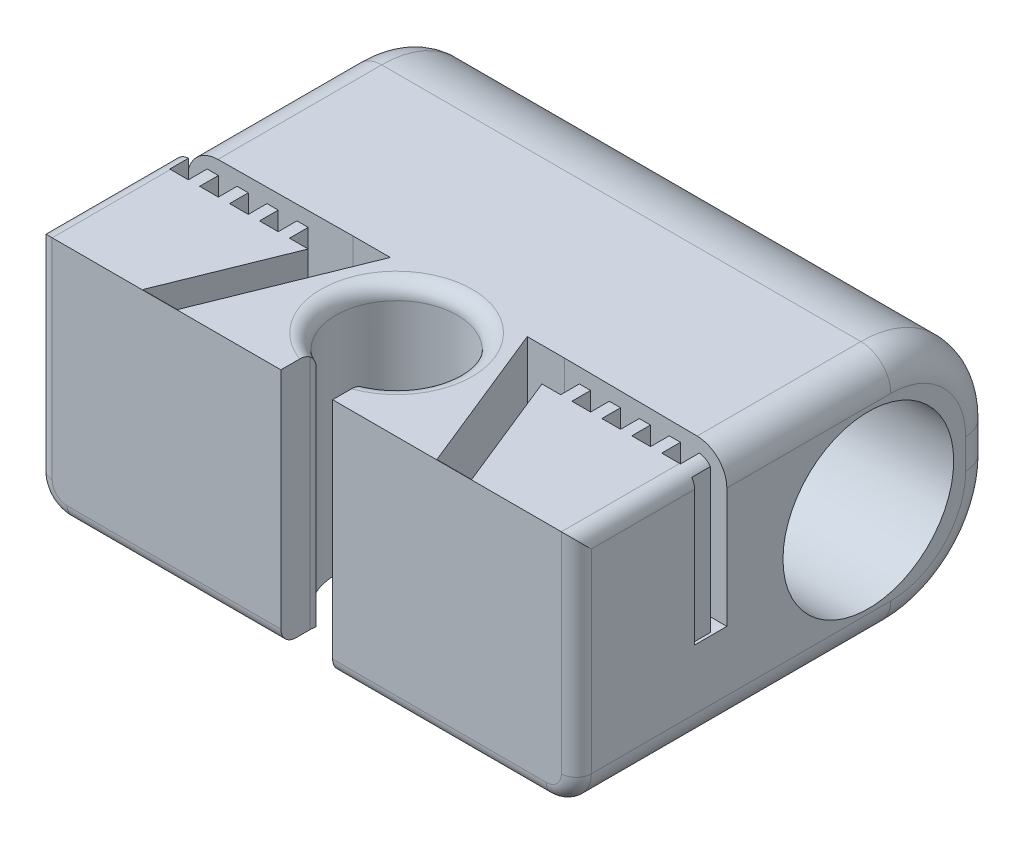
SolidWorks part; units mm, degrees
ref_plane "Alzado" through (0, 0, 0) normal (0, 0, 1) x (1, 0, 0)
ref_plane "Planta" through (0, 0, 0) normal (0, 1, 0) x (1, 0, 0)
ref_plane "Vista lateral" through (0, 0, 0) normal (1, 0, 0) x (0, 0, -1)
sketch "Croquis1" plane through (0, 0, 0) normal (0, 1, 0) x (1, 0, 0)
  line L0 (-16.125, -12.8625) -> (37.0847, -12.8625) construction
  line L1 (-16.125, 9.1375) -> (19.875, 9.1375)
  line L2 (-16.125, 9.1375) -> (-16.125, -18.8625)
  line L3 (-16.125, -18.8625) -> (0.1467, -18.8625)
  line L4 (19.875, 9.1375) -> (19.875, -18.8625)
  line L5 (19.875, 9.1375) -> (-16.125, -18.8625) construction
  line L6 (1.875, -16.9125) -> (1.875, -18.8125) construction
  line L7 (3.6033, -16.9125) -> (3.6033, -18.8625)
  line L8 (0.1467, -16.9125) -> (0.1467, -18.8625)
  line L9 (3.6033, -18.8625) -> (19.875, -18.8625)
  line L10 (-16.1265, 0.6375) -> (22.0746, 0.6375) construction
  line L11 (1.875, -12.8625) -> (1.875, 9.1375) construction
  arc A0 (3.5635, -16.5437) -> (0.1865, -16.5437) centre (1.875, -12.8625) ccw
  arc A1 (3.6033, -16.9125) -> (3.5635, -16.5437) centre (1.875, -16.9125) ccw
  arc A3 (0.1865, -16.5437) -> (0.1467, -16.9125) centre (1.875, -16.9125) ccw
  point P10 (1.875, -17.8625)
  dimension "D4" = 3.4566
  dimension "D7" = 4.05
  dimension "D1" = 18
  dimension "D2" = 28
  dimension "D3" = 6
  dimension "D5" = 13.5
  dimension "D6" = 18
extrude "Saliente-Extruir1" add sketch "Croquis1" along normal blind 16
sketch "Croquis5" plane through (19.875, 0, 0) normal (1, 0, 0) x (0, 0, -1)
  line L0 (-12.8625, 19.8022) -> (-12.8625, -6.4895) construction
  line L1 (-18.8625, 16) -> (-18.8625, 0) construction
  line L2 (0.6375, 20.6011) -> (0.6375, -8.3415) construction
  line L3 (-18.8625, 8) -> (9.5862, 8) construction
  circle A0 centre (0.6375, 8) radius 5.7
  dimension "D3" = 11.4
  dimension "D1" = 6
  dimension "D2" = 13.5
extrude "Cortar-Extruir1" cut sketch "Croquis5" against normal blind 38
sketch "Croquis8" plane through (0, 0, 0) normal (0, -1, 0) x (1, 0, 0)
  line L2 (-2.175, 12.8625) -> (5.925, 12.8625)
  arc A0 (0.1865, 16.5437) -> (3.5635, 16.5437) centre (1.875, 12.8625) ccw construction
  arc A1 (-2.175, 12.8625) -> (5.925, 12.8625) centre (1.875, 12.8625) ccw
extrude "Saliente-Extruir2" add sketch "Croquis8" against normal blind 0.6
sketch "Croquis9" plane through (0, 16, 0) normal (0, 1, 0) x (1, 0, 0)
  line L0 (1.875, -12.8625) -> (1.875, 4.8397) construction
  line L1 (5.925, -12.8625) -> (-2.175, -12.8625) construction
  line L2 (-2.175, -12.8625) -> (-2.175, 5.5668) construction
  line L3 (-15.9292, -9.7125) -> (-15.9292, -10.9625)
  line L4 (-15.1792, -9.7125) -> (-15.9292, -9.7125)
  line L5 (-15.1792, -10.9625) -> (-15.1792, -9.7125)
  line L6 (-13.9292, -10.9625) -> (-15.1792, -10.9625)
  line L7 (-13.9292, -9.7125) -> (-13.9292, -10.9625)
  line L8 (-13.1792, -9.7125) -> (-13.9292, -9.7125)
  line L9 (-13.1792, -10.9625) -> (-13.1792, -9.7125)
  line L10 (-11.9292, -10.9625) -> (-13.1792, -10.9625)
  line L11 (-11.9292, -9.7125) -> (-11.9292, -10.9625)
  line L12 (-11.1792, -9.7125) -> (-11.9292, -9.7125)
  line L13 (-11.1792, -10.9625) -> (-11.1792, -9.7125)
  line L14 (-9.9292, -10.9625) -> (-11.1792, -10.9625)
  line L15 (-9.9292, -9.7125) -> (-9.9292, -10.9625)
  line L16 (-9.9292, -9.7125) -> (-9.1792, -9.7125)
  line L17 (-9.1792, -9.7125) -> (-9.1792, -10.9625)
  line L18 (-7.9292, -10.9625) -> (-9.1792, -10.9625)
  line L19 (-7.9292, -10.9625) -> (-7.9292, -9.7125)
  line L20 (-7.9292, -9.7125) -> (-7.1792, -9.7125)
  line L21 (1.875, -8.8125) -> (-16.125, -8.8125) construction
  line L22 (-7.1792, -9.7125) -> (-7.1792, -10.9625)
  line L23 (-5.9292, -10.9625) -> (-7.1792, -10.9625)
  line L24 (-5.9292, -10.9625) -> (-9.1129, -18.8425)
  line L25 (-2.7007, -8.7125) -> (-6.7935, -18.8425)
  line L26 (-5.1792, -8.7125) -> (-2.7007, -8.7125)
  line L27 (-5.1792, -8.7125) -> (-16.125, -8.8125)
  line L28 (-16.125, 9.1375) -> (-16.125, -18.8625) construction
  line L29 (-16.125, -8.8125) -> (-16.125, -10.9625)
  line L30 (-15.9292, -10.9625) -> (-16.125, -10.9625)
  line L31 (-9.1129, -18.8425) -> (-6.7935, -18.8425)
  line L32 (12.8629, -18.8425) -> (10.5435, -18.8425)
  line L33 (19.6792, -10.9625) -> (19.875, -10.9625)
  line L34 (19.875, -8.8125) -> (19.875, -10.9625)
  line L35 (8.9292, -8.7125) -> (19.875, -8.8125)
  line L36 (8.9292, -8.7125) -> (6.4507, -8.7125)
  line L37 (6.4507, -8.7125) -> (10.5435, -18.8425)
  line L38 (9.6792, -10.9625) -> (12.8629, -18.8425)
  line L39 (9.6792, -10.9625) -> (10.9292, -10.9625)
  line L40 (10.9292, -9.7125) -> (10.9292, -10.9625)
  line L41 (11.6792, -9.7125) -> (10.9292, -9.7125)
  line L42 (11.6792, -10.9625) -> (11.6792, -9.7125)
  line L43 (11.6792, -10.9625) -> (12.9292, -10.9625)
  line L44 (12.9292, -9.7125) -> (12.9292, -10.9625)
  line L45 (13.6792, -9.7125) -> (12.9292, -9.7125)
  line L46 (13.6792, -9.7125) -> (13.6792, -10.9625)
  line L47 (13.6792, -10.9625) -> (14.9292, -10.9625)
  line L48 (14.9292, -10.9625) -> (14.9292, -9.7125)
  line L49 (14.9292, -9.7125) -> (15.6792, -9.7125)
  line L50 (15.6792, -9.7125) -> (15.6792, -10.9625)
  line L51 (15.6792, -10.9625) -> (16.9292, -10.9625)
  line L52 (16.9292, -10.9625) -> (16.9292, -9.7125)
  line L53 (16.9292, -9.7125) -> (17.6792, -9.7125)
  line L54 (17.6792, -9.7125) -> (17.6792, -10.9625)
  line L55 (17.6792, -10.9625) -> (18.9292, -10.9625)
  line L56 (18.9292, -10.9625) -> (18.9292, -9.7125)
  line L57 (18.9292, -9.7125) -> (19.6792, -9.7125)
  line L58 (19.6792, -9.7125) -> (19.6792, -10.9625)
  arc A0 (3.5635, -16.5437) -> (0.1865, -16.5437) centre (1.875, -12.8625) ccw construction
  arc A1 (5.925, -12.8625) -> (-2.175, -12.8625) centre (1.875, -12.8625) ccw construction
extrude "Cortar-Extruir2" cut sketch "Croquis9" against normal blind 10
fillet "Redondeo1" radius 7 2 edges at (1.875, 16, -9.1375) (1.875, 0, -9.1375)
fillet "Redondeo2" radius 2 10 edges at (-16.125, 16, 3.3375) (-16.125, 13.9497, -7.0872) (-16.125, 8, -9.1375) (-16.125, 2.0503, -7.0872) (19.875, 0, 8.3625) (19.875, 16, 3.3375) (-16.125, 0, 8.3625) (19.875, 2.0503, -7.0872) (19.875, 8, -9.1375) (19.875, 13.9497, -7.0872)
fillet "Redondeo3" radius 1 1 edges at (1.875, 16, 8.8125)
fillet "Redondeo5" radius 1 8 edges at (10.7391, 0, 18.8625) (19.2892, 0.5858, 18.8625) (-6.9891, 0, 18.8625) (-15.5392, 0.5858, 18.8625) (19.875, 9, 18.8625) (-16.125, 9, 18.8625) (-16.125, 16, 14.9125) (19.875, 16, 14.9125)
sketch "Croquis10" plane through (-16.125, 0, 0) normal (-1, 0, 0) x (0, 0, 1)
  circle A0 centre (-0.6375, 8) radius 5.7 construction
  circle A1 centre (-0.6375, 8) radius 5.7
  circle A2 centre (-0.6375, 8) radius 4.7
extrude "Saliente-Extruir3" add sketch "Croquis10" against normal blind 2
